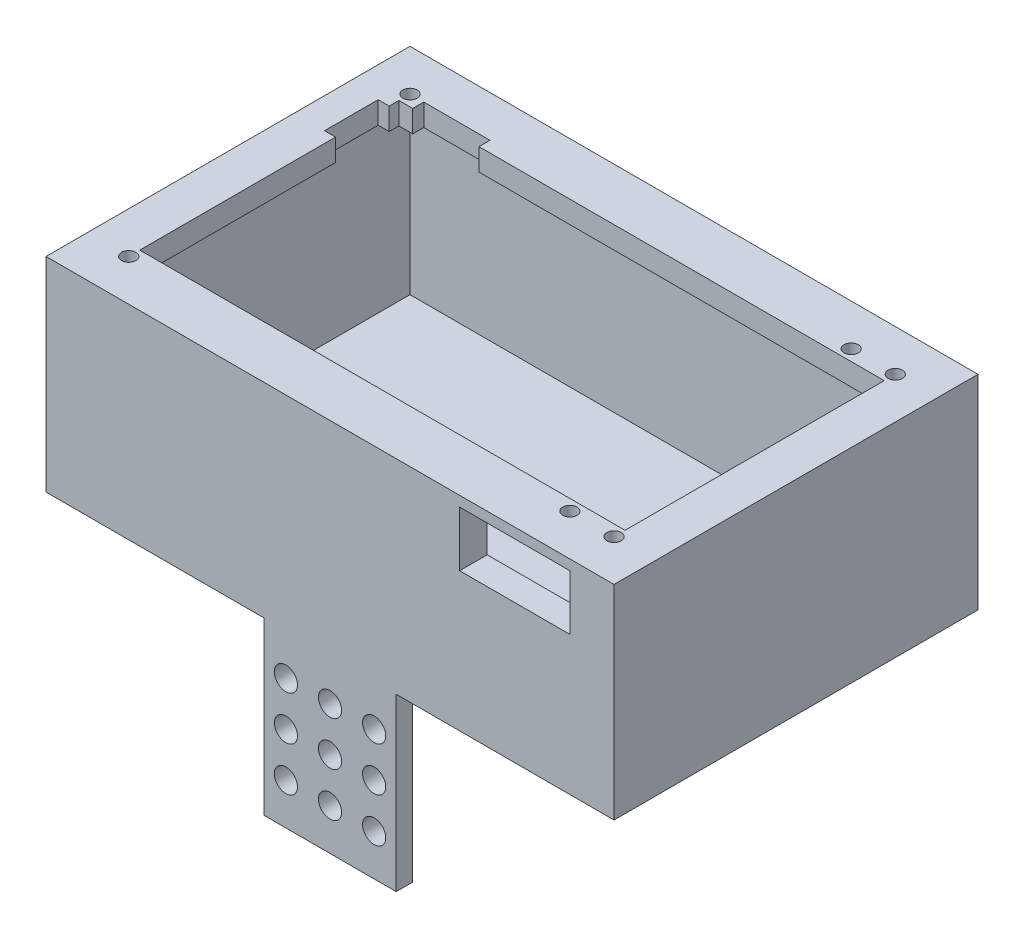
SolidWorks part; units mm, degrees
ref_plane "前基準面" through (0, 0, 0) normal (0, 0, 1) x (1, 0, 0)
ref_plane "上基準面" through (0, 0, 0) normal (0, 1, 0) x (1, 0, 0)
ref_plane "右基準面" through (0, 0, 0) normal (1, 0, 0) x (0, 0, -1)
sketch "草圖1" plane through (0, 0, 0) normal (0, 1, 0) x (1, 0, 0)
  line L1 (0, 0) -> (93, 0)
  line L2 (0, 0) -> (0, 56)
  line L3 (0, 56) -> (93, 56)
  line L4 (93, 0) -> (93, 56)
  dimension "D1" = 56
  dimension "D2" = 93
extrude "填料-伸長1" add sketch "草圖1" along normal blind 4
sketch "草圖2" plane through (0, 4, 0) normal (0, 1, 0) x (1, 0, 0)
  line L0 (0, 56) -> (0, 0) construction
  line L1 (93, 56) -> (0, 56) construction
  line L2 (93, 0) -> (93, 56) construction
  line L3 (0, 0) -> (93, 0) construction
  circle A0 centre (90.5, 53.5) radius 1.3
  circle A1 centre (90.5, 2.5) radius 1.3
  circle A3 centre (2.5, 53.5) radius 1.3
  circle A4 centre (2.5, 2.5) radius 1.3
  circle A6 centre (82.5, 2.5) radius 1.3
  circle A7 centre (82.5, 53.5) radius 1.3
  dimension "D1" = 2.6
  dimension "D14" = 2.6
  dimension "D15" = 2.6
  dimension "D17" = 2.6
  dimension "D18" = 2.6
  dimension "D19" = 2.6
  dimension "D3" = 2.5
  dimension "D4" = 2.5
  dimension "D5" = 2.5
  dimension "D6" = 2.5
  dimension "D7" = 2.5
  dimension "D8" = 2.5
  dimension "D9" = 2.5
  dimension "D12" = 2.5
  dimension "D20" = 2.5
  dimension "D21" = 8
  dimension "D22" = 8
extrude "除料-伸長1" cut sketch "草圖2" against normal blind 4
sketch "草圖3" plane through (0, 4, 0) normal (0, 1, 0) x (1, 0, 0)
  line L5 (93, 0) -> (98, 0)
  line L6 (93, 0) -> (93, 56)
  line L7 (93, 56) -> (98, 56)
  line L8 (98, 0) -> (98, 56)
  line L13 (0, 56) -> (-5, 56)
  line L14 (0, 56) -> (0, 0)
  line L15 (0, 0) -> (-5, 0)
  line L16 (-5, 56) -> (-5, 0)
  line L17 (-5, 56) -> (98, 56)
  line L18 (-5, 56) -> (-5, 61)
  line L19 (-5, 61) -> (98, 61)
  line L20 (98, 56) -> (98, 61)
  line L21 (-5, 0) -> (98, 0)
  line L22 (-5, 0) -> (-5, -5)
  line L23 (-5, -5) -> (98, -5)
  line L24 (98, 0) -> (98, -5)
  line M16 (0, 56) -> (0, 0)
  line M17 (0, 0) -> (93, 0)
  line M18 (93, 0) -> (93, 56)
  line M19 (93, 56) -> (0, 56)
  dimension "D1" = 5
  dimension "D2" = 5
  dimension "D3" = 5
  dimension "D4" = 5
extrude "填料-伸長2" add sketch "草圖3" against normal blind 34 contours L13 L16 L15 M16 | L7 L20 L19 L18 L13 M19 | L5 L8 L7 M18 | L24 L5 L15 L22 L23 M17
sketch "草圖4" plane through (0, -30, 0) normal (0, -1, 0) x (-1, 0, 0)
  line L1 (5, -5) -> (-98, -5)
  line L2 (5, -5) -> (5, 61)
  line L3 (5, 61) -> (-98, 61)
  line L4 (-98, -5) -> (-98, 61)
extrude "填料-伸長3" add sketch "草圖4" along normal blind 3
sketch "草圖5" plane through (0, 4, 0) normal (0, 1, 0) x (1, 0, 0)
  line L0 (-5, 61) -> (-5, -5) construction
  line L1 (2.5, 51.5) -> (5, 51.5)
  line L2 (2.5, 51.5) -> (2.5, 49.7335)
  line L3 (2.5, 4.5) -> (90.5, 4.5)
  line L4 (90.5, 51.5) -> (90.5, 4.5)
  line L5 (2.5, 40) -> (2.5, 4.5)
  line L6 (-5, 61) -> (98, 61) construction
  line L8 (5, 51.5) -> (5, 53.5)
  line L9 (5, 53.5) -> (17, 53.5)
  line L10 (17, 51.5) -> (17, 53.5)
  line L11 (2.5, 49.7335) -> (0.5, 49.7335)
  line L13 (2.5, 40) -> (0.5, 40)
  line L14 (0.5, 49.7335) -> (0.5, 40)
  line L15 (17, 51.5) -> (90.5, 51.5)
  dimension "D1" = 88
  dimension "D2" = 47
  dimension "D3" = 7.5
  dimension "D4" = 9.5
  dimension "D5" = 2
  dimension "D6" = 2
  dimension "D7" = 12
  dimension "D8" = 73.5
  dimension "D9" = 35.5
extrude "除料-伸長2" cut sketch "草圖5" against normal blind 21
sketch "草圖6" plane through (0, 0, 5) normal (0, 0, 1) x (1, 0, 0)
  line L0 (-5, 4) -> (98, 4) construction
  line L1 (34.5, 4) -> (58.5, 4)
  line L2 (34.5, 4) -> (34.5, -64)
  line L3 (34.5, -64) -> (58.5, -64)
  line L4 (58.5, 4) -> (58.5, -64)
  line L7 (-5, -33) -> (-5, 4) construction
  point P4 (34.5, 4)
  point P9 (0, 0)
  dimension "D1" = 68
  dimension "D2" = 24
  dimension "D4" = 39.5
extrude "填料-伸長4" add sketch "草圖6" against normal blind 5
sketch "草圖7" plane through (0, 0, 5) normal (0, 0, 1) x (1, 0, 0)
  circle A9 centre (38.5, -40.5) radius 2.1
  circle A10 centre (38.5, -48.5) radius 2.1
  circle A11 centre (38.5, -56.5) radius 2.1
  circle A12 centre (46.5, -40.5) radius 2.1
  circle A13 centre (46.5, -48.5) radius 2.1
  circle A14 centre (46.5, -56.5) radius 2.1
  circle A15 centre (54.5, -40.5) radius 2.1
  circle A16 centre (54.5, -48.5) radius 2.1
  circle A17 centre (54.5, -56.5) radius 2.1
  dimension "D14" = 8
  dimension "D24" = 4.2
  dimension "D25" = 4.2
  dimension "D26" = 4.2
  dimension "D15" = 8
  dimension "D17" = 3
extrude "除料-伸長3" cut sketch "草圖7" against normal blind 5
sketch "草圖9" plane through (0, 0, 0) normal (0, 0, -1) x (-1, 0, 0)
  line L1 (-58.5, -64) -> (-34.5, -64)
  line L2 (-58.5, -64) -> (-58.5, -33)
  line L3 (-58.5, -33) -> (-34.5, -33)
  line L4 (-34.5, -64) -> (-34.5, -33)
  circle A0 centre (-54.5, -40.5) radius 1.8
  circle A1 centre (-46.5, -40.5) radius 1.8
  circle A2 centre (-38.5, -40.5) radius 1.8
  circle A3 centre (-38.5, -48.5) radius 1.8
  circle A4 centre (-46.5, -48.5) radius 1.8
  circle A5 centre (-54.5, -48.5) radius 1.8
  circle A6 centre (-54.5, -56.5) radius 1.8
  circle A7 centre (-46.5, -56.5) radius 1.8
  circle A8 centre (-38.5, -56.5) radius 1.8
extrude "除料-伸長5" cut sketch "草圖9" against normal blind 2
sketch "草圖10" plane through (0, 0, 5) normal (0, 0, 1) x (1, 0, 0)
  line L0 (-5, -33) -> (-5, 4) construction
  line L1 (70, 2.15) -> (90, 2.15)
  line L2 (70, 2.15) -> (70, -7.85)
  line L3 (70, -7.85) -> (90, -7.85)
  line L4 (90, 2.15) -> (90, -7.85)
  line L5 (-5, 4) -> (98, 4) construction
  dimension "D1" = 20
  dimension "D2" = 10
  dimension "D3" = 75
  dimension "D4" = 1.85
extrude "除料-伸長6" cut sketch "草圖10" against normal blind 10
